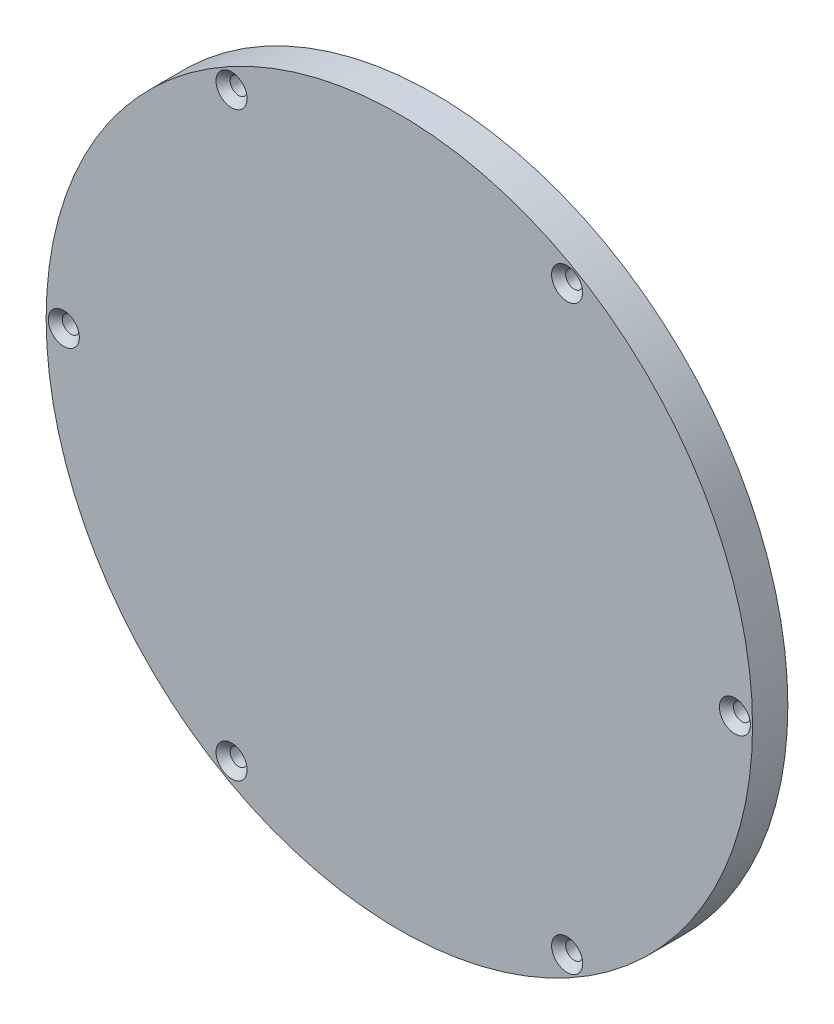
SolidWorks part; units mm, degrees
ref_plane "Front Plane" through (0, 0, 0) normal (0, 0, 1) x (1, 0, 0)
ref_plane "Top Plane" through (0, 0, 0) normal (0, 1, 0) x (1, 0, 0)
ref_plane "Right Plane" through (0, 0, 0) normal (1, 0, 0) x (0, 0, -1)
sketch "Sketch1" plane through (0, 0, 0) normal (0, 0, 1) x (1, 0, 0)
  circle A0 centre (0, 0) radius 50
  dimension "D1" = 100
extrude "Boss-Extrude1" add sketch "Sketch1" along normal blind 5
sketch "Sketch3" plane through (0, 0, 0) normal (0, 0, -1) x (-1, 0, 0)
  circle A0 centre (0, 0) radius 3
  dimension "D1" = 6
extrude "Cut-Extrude2" cut sketch "Sketch3" against normal blind 4
sketch "Sketch5" plane through (0, 0, 5) normal (0, 0, 1) x (1, 0, 0)
  line L0 (0, 0) -> (-47.5, 0) construction
  circle A0 centre (0, 0) radius 47.5 construction
hole_wizard "CSK for M2 Flat Head Machine Screw1" positions "3DSketch3" profile "Sketch8" countersink size "M2" standard "ANSI Metric" end condition through all
sketch3d "3DSketch3"
  point P0 (-47.5, 0, 5)
sketch "Sketch8" plane through (-47.5, 0, 5) normal (1, 0, 0) x (0, -1, 0)
  line L0 (0, 0) -> (0, 5)
  line L1 (0, 5) -> (1.2, 5)
  line L2 (1.2, 5) -> (1.2, 1)
  line L3 (1.2, 1) -> (2.2, 0)
  line L5 (2.2, 0) -> (0, 0)
  line L6 (-1.2, 1) -> (-2.2, 0) construction
  line L11 (0, -6.35) -> (0, 107.95) construction
  dimension "Thru Hole Dia." = 2.4
  dimension "Thru Hole Depth" = 5
  dimension "Near C'Sink Dia." = 4.4
  dimension "Near C'Sink Angle" = 90
pattern_circular "CirPattern1" count 6 over 360 about axis through (0, 0, 0) along (0, 0, 1) of "CSK for M2 Flat Head Machine Screw1"
